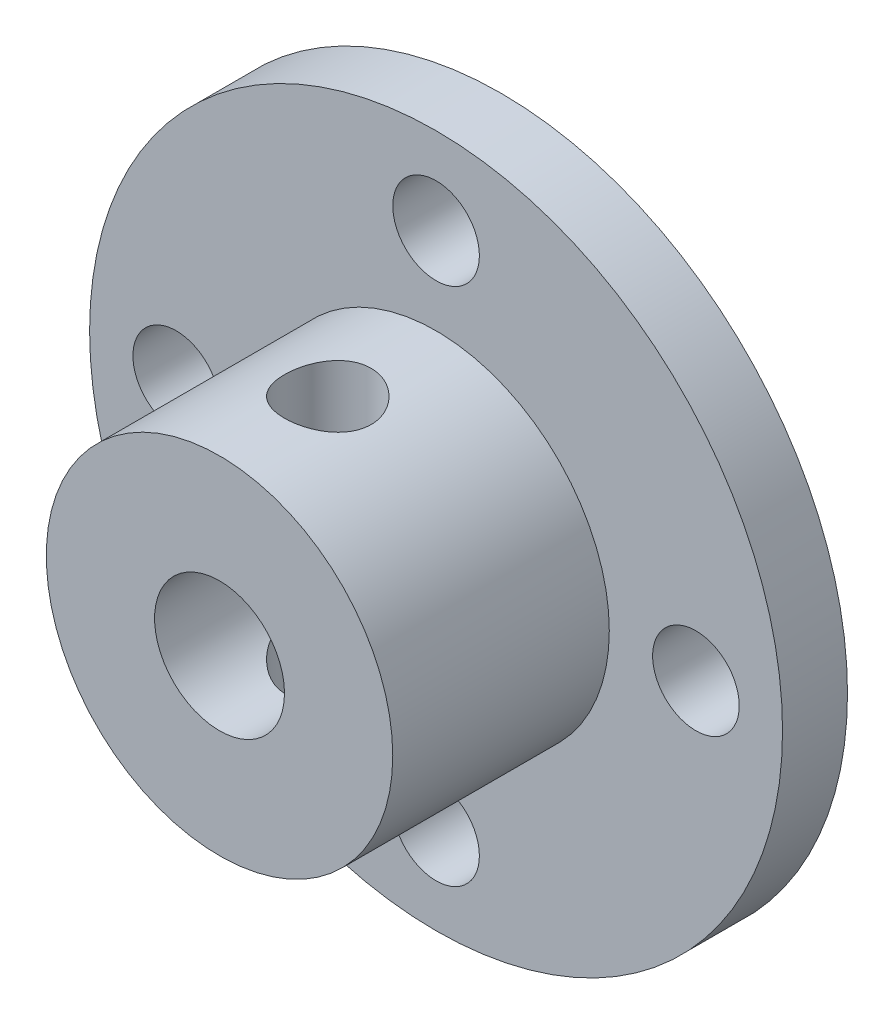
SolidWorks part; units mm, degrees
other "Markup1"
sketch "Sketch5" plane through (16, 16, 13) normal (0.1539, 0.7537, 0.639) x (0.5798, 0.4547, -0.6761)
ref_plane "Front Plane" through (0, 0, 0) normal (0, 0, 1) x (1, 0, 0)
ref_plane "Top Plane" through (0, 0, 0) normal (0, 1, 0) x (1, 0, 0)
ref_plane "Right Plane" through (0, 0, 0) normal (1, 0, 0) x (0, 0, -1)
sketch "Sketch1" plane through (0, 0, 0) normal (0, 0, 1) x (1, 0, 0)
  circle A0 centre (0, 0) radius 16
  dimension "D1" = 32
extrude "Boss-Extrude1" add sketch "Sketch1" along normal blind 3
sketch "Sketch2" plane through (0, 0, 3) normal (0, 0, 1) x (1, 0, 0)
  circle A0 centre (0, 0) radius 8
  circle A1 centre (0, 0) radius 3
  dimension "D1" = 6
  dimension "D2" = 16
extrude "Boss-Extrude2" add sketch "Sketch2" along normal blind 10
sketch "Sketch3" plane through (0, 0, 3) normal (0, 0, 1) x (1, 0, 0)
  line L0 (0, 0) -> (0, 12) construction
  line L1 (-12, 0) -> (0, 0) construction
  line L2 (12, 0) -> (0, 0) construction
  line L3 (0, 0) -> (0, -12) construction
  circle A0 centre (0, 12) radius 2
  circle A4 centre (12, 0) radius 2
  circle A5 centre (0, -12) radius 2
  circle A6 centre (-12, 0) radius 2
  dimension "D2" = 4
  dimension "D3" = 12
  dimension "D4" = 4
  dimension "D5" = 4
  dimension "D6" = 12
  dimension "D7" = 12
  dimension "D8" = 4
  dimension "D1" = 12
extrude "Cut-Extrude1" cut sketch "Sketch3" against normal through all
sketch "Sketch4" plane through (0, 0, 0) normal (0, 1, 0) x (1, 0, 0)
  line L0 (-8, -13) -> (8, -13) construction
  line L1 (8, -13) -> (8, -3) construction
  circle A0 centre (0, -8) radius 2
  dimension "D1" = 5
  dimension "D2" = 4
  dimension "D3" = 8
extrude "Cut-Extrude2" cut sketch "Sketch4" against normal through all both and the other way through all
